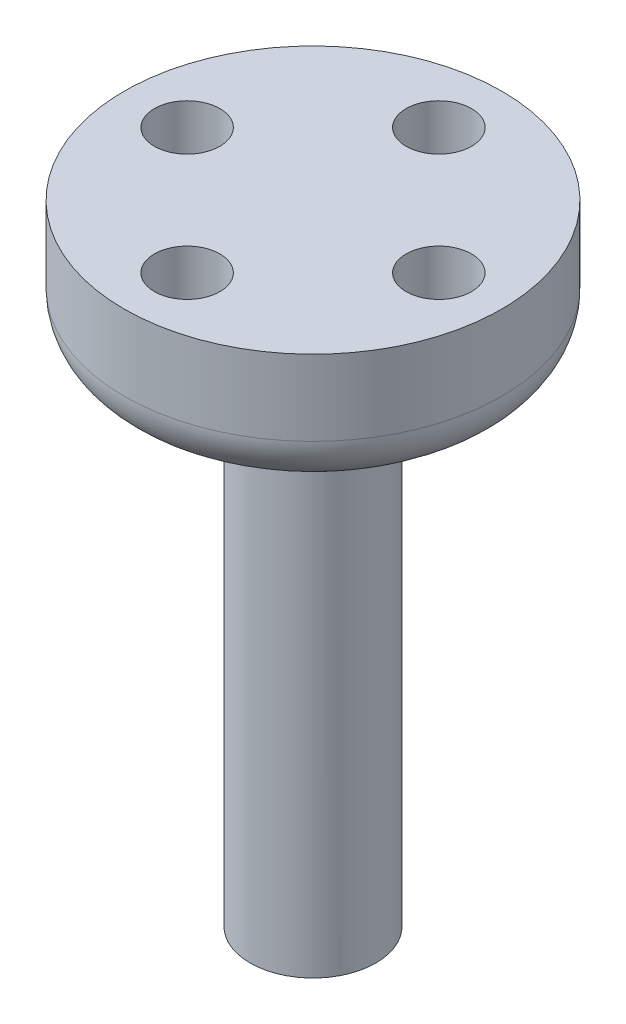
SolidWorks part; units mm, degrees
ref_plane "Front Plane" through (0, 0, 0) normal (0, 0, 1) x (1, 0, 0)
ref_plane "Top Plane" through (0, 0, 0) normal (0, 1, 0) x (1, 0, 0)
ref_plane "Right Plane" through (0, 0, 0) normal (1, 0, 0) x (0, 0, -1)
sketch "Sketch1" plane through (0, 0, 0) normal (0, 1, 0) x (1, 0, 0)
  circle A6 centre (0, 0) radius 7.5
  dimension "D4" = 15
extrude "Boss-Extrude1" add sketch "Sketch1" along normal blind 5
sketch "Sketch2" plane through (0, 5, 0) normal (0, 1, 0) x (1, 0, 0)
  circle A0 centre (0, 0) radius 5 construction
  circle A1 centre (0, 5) radius 1.3
  circle A2 centre (5, 0) radius 1.3
  circle A3 centre (0, -5) radius 1.3
  circle A4 centre (-5, 0) radius 1.3
  dimension "D1" = 2.6
  dimension "D2" = 10
extrude "Cut-Extrude1" cut sketch "Sketch2" against normal blind 3
fillet "Fillet1" radius 2 1 edges at (0, 0, 7.5)
sketch "Sketch3" plane through (0, 0, 0) normal (0, -1, 0) x (1, 0, 0)
  circle A0 centre (0, 0) radius 2.5
  dimension "D1" = 5
extrude "Boss-Extrude2" add sketch "Sketch3" along normal blind 20
